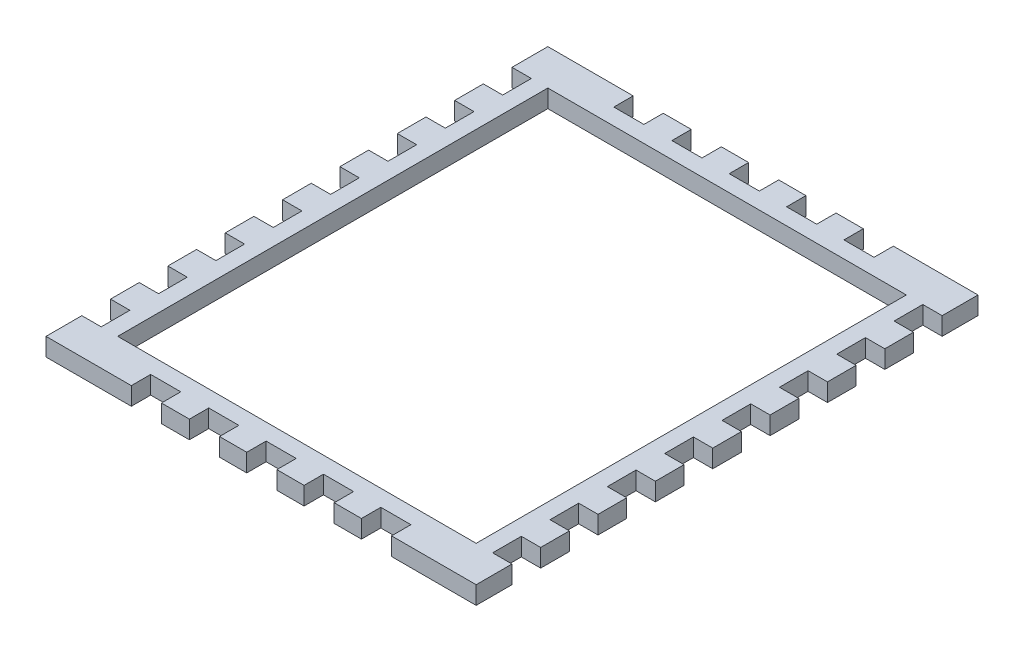
SolidWorks part; units mm, degrees
ref_plane "Front Plane" through (0, 0, 0) normal (0, 0, 1) x (1, 0, 0)
ref_plane "Top Plane" through (0, 0, 0) normal (0, 1, 0) x (1, 0, 0)
ref_plane "Right Plane" through (0, 0, 0) normal (1, 0, 0) x (0, 0, -1)
sketch "Sketch1" plane through (0, 0, 0) normal (0, 1, 0) x (1, 0, 0)
  line L1 (-38.1, -44.45) -> (38.1, -44.45)
  line L2 (-38.1, -44.45) -> (-38.1, 44.45)
  line L3 (-38.1, 44.45) -> (38.1, 44.45)
  line L4 (38.1, -44.45) -> (38.1, 44.45)
  line L5 (-38.1, -44.45) -> (38.1, 44.45) construction
  line L6 (-38.1, 44.45) -> (38.1, -44.45) construction
  line L11 (-31.75, -38.1) -> (-31.75, -41.275) construction
  line L12 (-31.75, -38.1) -> (31.75, -38.1)
  line L13 (-31.75, -38.1) -> (-31.75, 38.1)
  line L14 (-31.75, 38.1) -> (31.75, 38.1)
  line L15 (31.75, -38.1) -> (31.75, 38.1)
  line L16 (-34.925, -38.1) -> (-31.75, -38.1) construction
  line L17 (31.75, 38.1) -> (31.75, 41.275) construction
  line L18 (31.75, 38.1) -> (34.925, 38.1) construction
  point P0 (0, 0)
  dimension "D3" = 6.35
  dimension "D1" = 76.2
  dimension "D2" = 88.9
  dimension "D4" = 6.35
  dimension "D5" = 6.35
  dimension "D6" = 3.175
  dimension "D7" = 6.35
extrude "Boss-Extrude1" add sketch "Sketch1" along normal blind 3.175
sketch "Sketch2" plane through (0, 0, 0) normal (0, 1, 0) x (1, 0, 0)
  line L29 (0, 0) -> (11.4095, 0) construction
  line L31 (17.78, -44.45) -> (23.114, -44.45)
  line L32 (7.62, -44.45) -> (12.954, -44.45)
  line L33 (-2.54, -44.45) -> (2.794, -44.45)
  line L34 (-12.7, -44.45) -> (-7.366, -44.45)
  line L35 (-22.987, -44.45) -> (-17.653, -44.45)
  line L39 (23.114, -41.021) -> (23.114, -44.45)
  line L40 (17.78, -41.021) -> (23.114, -41.021)
  line L41 (17.78, -44.45) -> (17.78, -41.021)
  line L42 (12.954, -41.021) -> (12.954, -44.45)
  line L43 (7.62, -41.021) -> (12.954, -41.021)
  line L44 (7.62, -44.45) -> (7.62, -41.021)
  line L45 (2.794, -41.021) -> (2.794, -44.45)
  line L46 (-2.54, -41.021) -> (2.794, -41.021)
  line L47 (-2.54, -44.45) -> (-2.54, -41.021)
  line L48 (-7.366, -41.021) -> (-7.366, -44.45)
  line L49 (-12.7, -41.021) -> (-7.366, -41.021)
  line L50 (-12.7, -44.45) -> (-12.7, -41.021)
  line L51 (-17.653, -41.021) -> (-17.653, -44.45)
  line L52 (-22.987, -41.021) -> (-17.653, -41.021)
  line L53 (-22.987, -44.45) -> (-22.987, -41.021)
  line L58 (-38.1, 44.45) -> (-38.1, -44.45) construction
  line L59 (-38.1, 38.1) -> (-34.671, 38.1)
  line L60 (-38.1, 38.1) -> (-38.1, 33.02)
  line L61 (-38.1, 33.02) -> (-34.671, 33.02)
  line L62 (-34.671, 38.1) -> (-34.671, 33.02)
  line L63 (-38.1, 27.94) -> (-34.671, 27.94)
  line L64 (-38.1, 27.94) -> (-38.1, 22.86)
  line L65 (-38.1, 22.86) -> (-34.671, 22.86)
  line L66 (-34.671, 27.94) -> (-34.671, 22.86)
  line L67 (-38.1, 17.78) -> (-34.671, 17.78)
  line L68 (-38.1, 17.78) -> (-38.1, 12.7)
  line L69 (-38.1, 12.7) -> (-34.671, 12.7)
  line L70 (-34.671, 17.78) -> (-34.671, 12.7)
  line L71 (-38.1, 7.62) -> (-34.671, 7.62)
  line L72 (-38.1, 7.62) -> (-38.1, 2.54)
  line L73 (-38.1, 2.54) -> (-34.671, 2.54)
  line L74 (-34.671, 7.62) -> (-34.671, 2.54)
  line L75 (-38.1, -2.54) -> (-34.671, -2.54)
  line L76 (-38.1, -2.54) -> (-38.1, -7.62)
  line L77 (-38.1, -7.62) -> (-34.671, -7.62)
  line L78 (-34.671, -2.54) -> (-34.671, -7.62)
  line L79 (-38.1, -12.7) -> (-34.671, -12.7)
  line L80 (-38.1, -12.7) -> (-38.1, -17.78)
  line L81 (-38.1, -17.78) -> (-34.671, -17.78)
  line L82 (-34.671, -12.7) -> (-34.671, -17.78)
  line L83 (-38.1, -22.86) -> (-34.671, -22.86)
  line L84 (-38.1, -22.86) -> (-38.1, -27.94)
  line L85 (-38.1, -27.94) -> (-34.671, -27.94)
  line L86 (-34.671, -22.86) -> (-34.671, -27.94)
  line L87 (-38.1, -33.02) -> (-34.671, -33.02)
  line L88 (-38.1, -33.02) -> (-38.1, -38.1)
  line L89 (-38.1, -38.1) -> (-34.671, -38.1)
  line L90 (-34.671, -33.02) -> (-34.671, -38.1)
  line L91 (0, 0) -> (0, 13.7627) construction
  line L92 (34.671, -33.02) -> (34.671, -38.1)
  line L93 (38.1, -38.1) -> (34.671, -38.1)
  line L94 (38.1, -33.02) -> (38.1, -38.1)
  line L95 (38.1, -33.02) -> (34.671, -33.02)
  line L96 (34.671, -22.86) -> (34.671, -27.94)
  line L97 (38.1, -27.94) -> (34.671, -27.94)
  line L98 (38.1, -22.86) -> (38.1, -27.94)
  line L99 (38.1, -22.86) -> (34.671, -22.86)
  line L100 (34.671, -12.7) -> (34.671, -17.78)
  line L101 (38.1, -17.78) -> (34.671, -17.78)
  line L102 (38.1, -12.7) -> (38.1, -17.78)
  line L103 (38.1, -12.7) -> (34.671, -12.7)
  line L104 (34.671, -2.54) -> (34.671, -7.62)
  line L105 (38.1, -7.62) -> (34.671, -7.62)
  line L106 (38.1, -2.54) -> (38.1, -7.62)
  line L107 (38.1, -2.54) -> (34.671, -2.54)
  line L108 (34.671, 7.62) -> (34.671, 2.54)
  line L109 (38.1, 2.54) -> (34.671, 2.54)
  line L110 (38.1, 7.62) -> (38.1, 2.54)
  line L111 (38.1, 7.62) -> (34.671, 7.62)
  line L112 (34.671, 17.78) -> (34.671, 12.7)
  line L113 (38.1, 12.7) -> (34.671, 12.7)
  line L114 (38.1, 17.78) -> (38.1, 12.7)
  line L115 (38.1, 17.78) -> (34.671, 17.78)
  line L116 (34.671, 27.94) -> (34.671, 22.86)
  line L117 (38.1, 22.86) -> (34.671, 22.86)
  line L118 (38.1, 27.94) -> (38.1, 22.86)
  line L119 (38.1, 27.94) -> (34.671, 27.94)
  line L120 (34.671, 38.1) -> (34.671, 33.02)
  line L121 (38.1, 33.02) -> (34.671, 33.02)
  line L122 (38.1, 38.1) -> (38.1, 33.02)
  line L123 (38.1, 38.1) -> (34.671, 38.1)
  line L124 (38.1, 44.45) -> (-38.1, 44.45) construction
  line L126 (-22.987, 44.45) -> (-22.987, 41.021)
  line L127 (-22.987, 41.021) -> (-17.653, 41.021)
  line L128 (-17.653, 41.021) -> (-17.653, 44.45)
  line L129 (-12.7, 44.45) -> (-12.7, 41.021)
  line L130 (-12.7, 41.021) -> (-7.366, 41.021)
  line L131 (-7.366, 41.021) -> (-7.366, 44.45)
  line L132 (-2.54, 44.45) -> (-2.54, 41.021)
  line L133 (-2.54, 41.021) -> (2.794, 41.021)
  line L134 (2.794, 41.021) -> (2.794, 44.45)
  line L135 (7.62, 44.45) -> (7.62, 41.021)
  line L136 (7.62, 41.021) -> (12.954, 41.021)
  line L137 (12.954, 41.021) -> (12.954, 44.45)
  line L138 (17.78, 44.45) -> (17.78, 41.021)
  line L139 (17.78, 41.021) -> (23.114, 41.021)
  line L140 (23.114, 41.021) -> (23.114, 44.45)
  line L141 (-22.987, 44.45) -> (-17.653, 44.45)
  line L142 (-12.7, 44.45) -> (-7.366, 44.45)
  line L143 (-2.54, 44.45) -> (2.794, 44.45)
  line L144 (7.62, 44.45) -> (12.954, 44.45)
  line L145 (17.78, 44.45) -> (23.114, 44.45)
  point P1 (-34.671, 35.56)
  point P7 (-20.32, -44.45)
  point P8 (38.1, -35.56)
  dimension "D1" = 8.89
  dimension "D3" = 17.78
  dimension "D6" = 3.429
  dimension "D4" = 8.89
  dimension "D7" = 5.334
  dimension "D8" = 3.429
  dimension "D5" = 8
extrude "Cut-Extrude1" cut sketch "Sketch2" along normal through all
